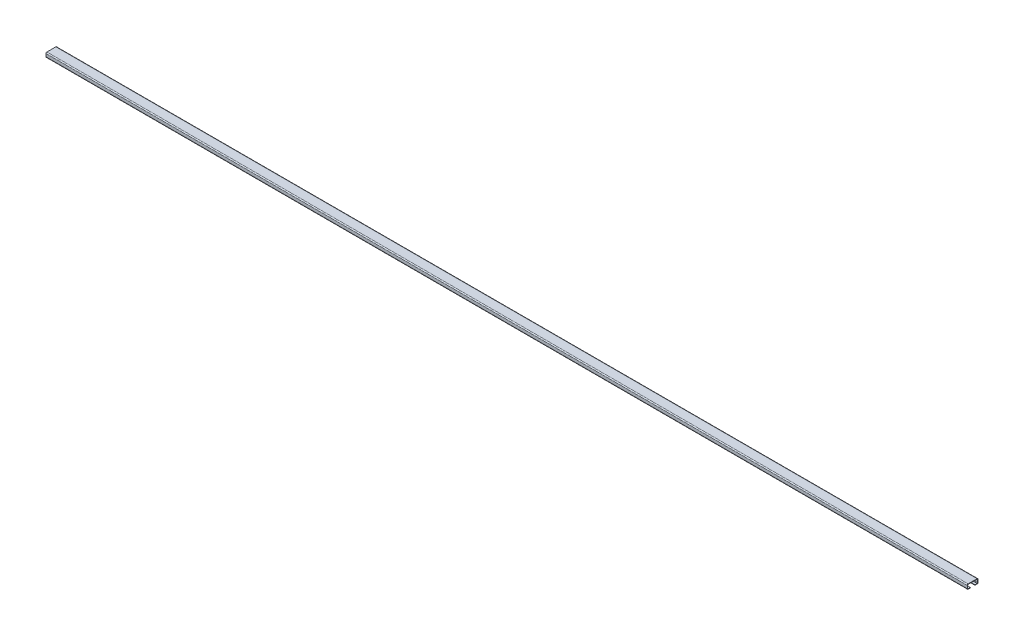
SolidWorks part; units mm, degrees
ref_plane "Plano frontal" through (0, 0, 0) normal (0, 0, 1) x (1, 0, 0)
ref_plane "Plano superior" through (0, 0, 0) normal (0, 1, 0) x (1, 0, 0)
ref_plane "Plano direito" through (0, 0, 0) normal (1, 0, 0) x (0, 0, -1)
sketch "Esboço1" plane through (0, 0, 0) normal (0, 0, 1) x (1, 0, 0)
  line L0 (3000, 0) -> (-3000, 0)
  point P4 (0, 0)
  dimension "D1" = 6000
other "Canal c 3 X 5(1)"
ref_plane "Plano1" through (3000, 0, 0) normal (-1, 0, 0) x (0, -1, 0)
sketch "Sketch110" plane through (3000, 0, 0) normal (-1, 0, 0) x (0, -1, 0)
  line L0 (0, -28.8) -> (0, 28.8)
  line L1 (6.2, 35) -> (23.8, 35)
  line L2 (6.2, -35) -> (23.8, -35)
  line L3 (30, -28.8) -> (30, -15)
  line L4 (30, 28.8) -> (30, 15)
  line L5 (27.25, -29.25) -> (27.25, -15)
  line L6 (5.75, -32.25) -> (24.25, -32.25)
  line L7 (2.75, -29.25) -> (2.75, 29.25)
  line L8 (5.75, 32.25) -> (24.25, 32.25)
  line L9 (27.25, 29.25) -> (27.25, 15)
  line L10 (27.25, 15) -> (30, 15)
  line L11 (27.25, -15) -> (30, -15)
  line L12 (2.75, 32.25) -> (27.25, 32.25) construction
  line L13 (27.25, 32.25) -> (27.25, 15) construction
  line L14 (2.75, -32.25) -> (2.75, 32.25) construction
  line L15 (2.75, -32.25) -> (27.25, -32.25) construction
  line L16 (27.25, -32.25) -> (27.25, -15) construction
  line L17 (30, -35) -> (30, -15) construction
  line L18 (0, -35) -> (30, -35) construction
  line L19 (0, -35) -> (0, 35) construction
  line L20 (0, 35) -> (30, 35) construction
  line L21 (30, 35) -> (30, 15) construction
  arc A0 (24.25, 32.25) -> (27.25, 29.25) centre (24.25, 29.25) cw
  arc A1 (2.75, 29.25) -> (5.75, 32.25) centre (5.75, 29.25) cw
  arc A2 (5.75, -32.25) -> (2.75, -29.25) centre (5.75, -29.25) cw
  arc A3 (27.25, -29.25) -> (24.25, -32.25) centre (24.25, -29.25) cw
  arc A4 (30, -28.8) -> (23.8, -35) centre (23.8, -28.8) cw
  arc A5 (0, -28.8) -> (6.2, -35) centre (6.2, -28.8) ccw
  arc A6 (6.2, 35) -> (0, 28.8) centre (6.2, 28.8) ccw
  arc A7 (23.8, 35) -> (30, 28.8) centre (23.8, 28.8) cw
  point P3 (0, 0)
  dimension "D4" = 2.75
  dimension "D5" = 3
  dimension "D2" = 30
  dimension "D6" = 6.2
  dimension "D1" = 70
